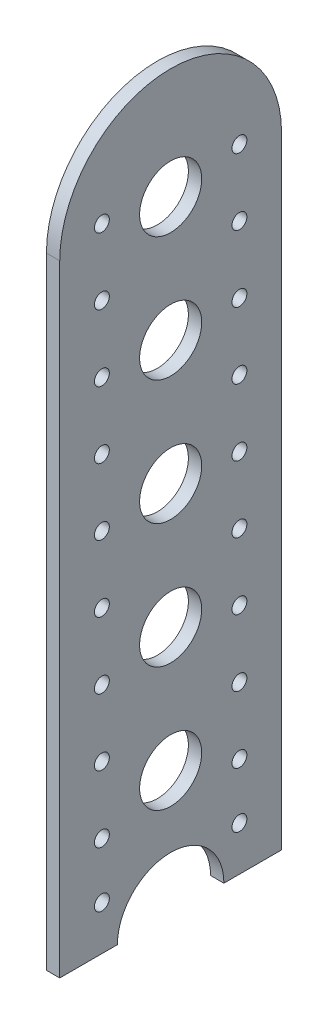
SolidWorks part; units mm, degrees
material "ABS"
ref_plane "Front Plane" through (0, 0, 0) normal (0, 0, 1) x (1, 0, 0)
ref_plane "Top Plane" through (0, 0, 0) normal (0, 1, 0) x (1, 0, 0)
ref_plane "Right Plane" through (0, 0, 0) normal (1, 0, 0) x (0, 0, -1)
sketch "Sketch1" plane through (0, 0, 0) normal (1, 0, 0) x (0, 0, -1)
  line B0 (-25.0949, -83.9552) -> (-12.0949, -83.9552)
  line B1 (-25.0949, -83.9552) -> (-25.0949, 56.0448)
  line B2 (24.9051, -83.9552) -> (24.9051, 56.0448)
  line B3 (11.9051, -83.9552) -> (24.9051, -83.9552)
  arc B4 (11.9051, -83.9552) -> (-12.0949, -83.9552) centre (-0.0949, -83.9552) ccw
  arc B5 (24.9051, 56.0448) -> (-25.0949, 56.0448) centre (-0.0949, 56.0448) ccw
  circle B6 centre (-0.0949, -55.9552) radius 7
  circle B7 centre (-0.0948, -27.9552) radius 7
  circle B8 centre (-0.0949, 0.0448) radius 7
  circle B9 centre (-0.0948, 28.0449) radius 6.9999
  circle B10 centre (-0.0949, 56.0447) radius 7
sketch_block_instance "Block1-1"
sketch_block "Block1"
extrude "Boss-Extrude1" add sketch "Sketch1" along normal blind 3
sketch "Sketch2" plane through (3, 0, 0) normal (1, 0, 0) x (0, 0, -1)
  line L0 (-25.0949, -83.9552) -> (-12.0949, -83.9552) construction
  line L1 (-25.0949, 56.0448) -> (-25.0949, -83.9552) construction
  line L2 (11.9051, -83.9552) -> (24.9051, -83.9552) construction
  line L3 (24.9051, -83.9552) -> (24.9051, 56.0448) construction
  circle A0 centre (-15.5949, -73.9552) radius 1.68
  circle A1 centre (15.4051, -73.9552) radius 1.68
  dimension "D1" = 10
  dimension "D3" = 10
  dimension "D2" = 9.5
  dimension "D4" = 9.5
sketch "Sketch4" plane through (3, 0, 0) normal (1, 0, 0) x (0, 0, -1)
  circle A0 centre (-15.5949, -61.4552) radius 1.68
  circle A1 centre (15.4051, -61.4552) radius 1.68
extrude "Cut-Extrude3" cut sketch "Sketch2" against normal through all
extrude "Cut-Extrude4" cut sketch "Sketch4" against normal through all
pattern_linear "LPattern2" count 9 spacing 15 along (0, 1, 0) of "Cut-Extrude4"
